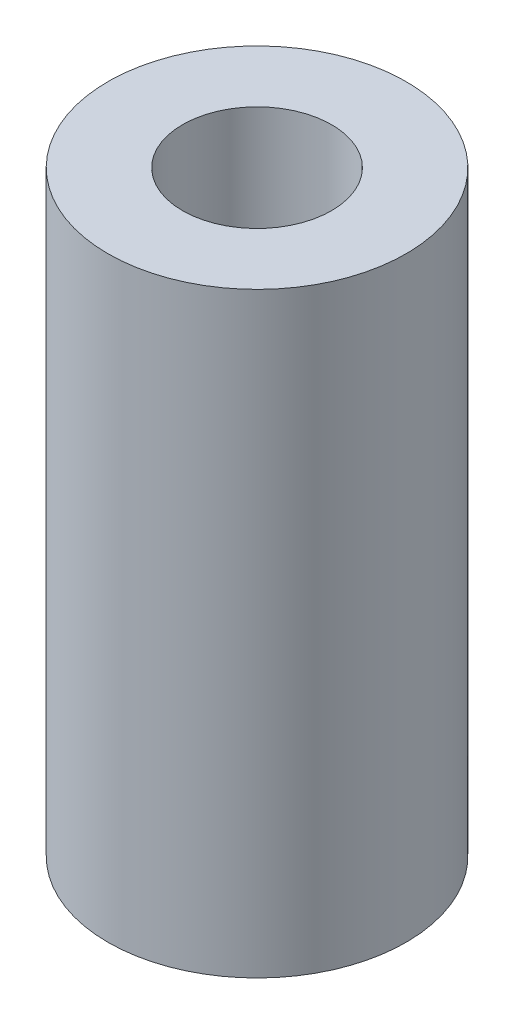
SolidWorks part; units mm, degrees
ref_plane "前视基准面" through (0, 0, 0) normal (0, 0, 1) x (1, 0, 0)
ref_plane "上视基准面" through (0, 0, 0) normal (0, 1, 0) x (1, 0, 0)
ref_plane "右视基准面" through (0, 0, 0) normal (1, 0, 0) x (0, 0, -1)
sketch "Sketch1" plane through (0, 0, 0) normal (0, 1, 0) x (1, 0, 0)
  circle A0 centre (0, 0) radius 4
  circle A1 centre (0, 0) radius 2
  dimension "D1" = 4
  dimension "D2" = 8
extrude "Boss-Extrude1" add sketch "Sketch1" along normal mid plane 16
